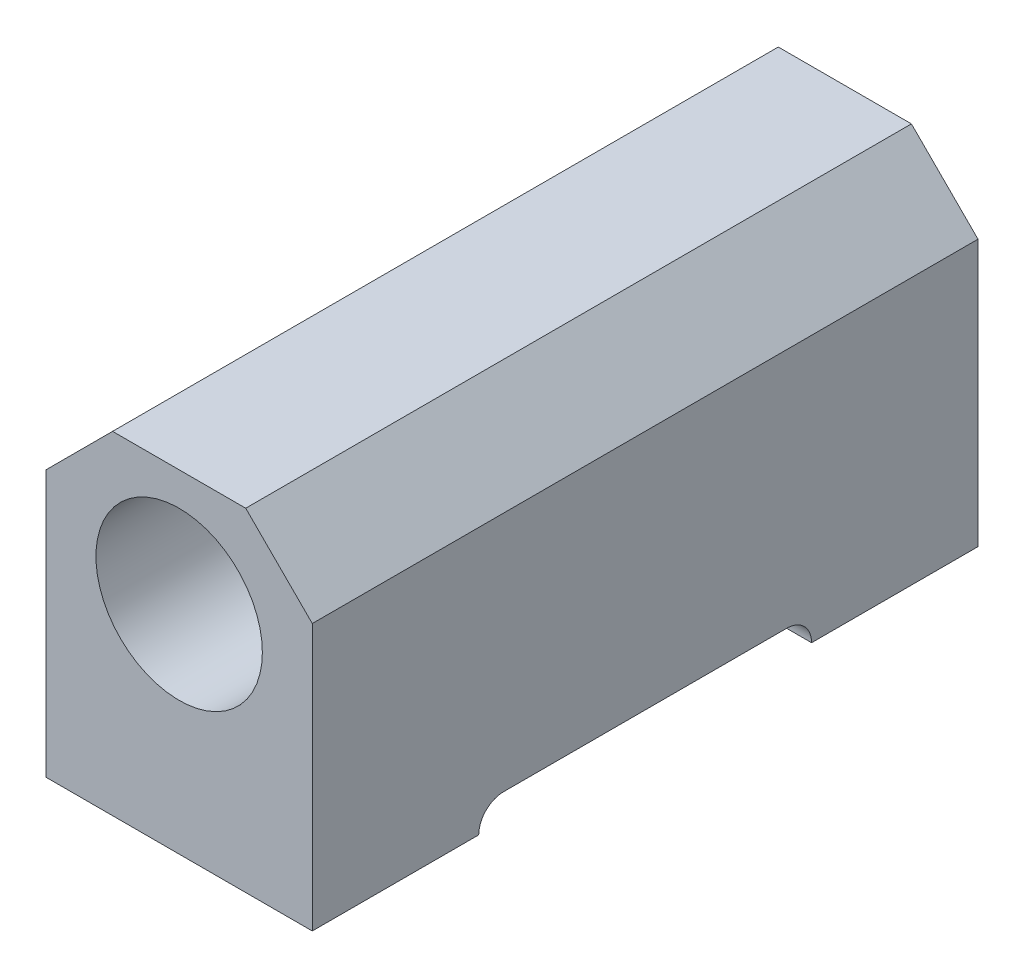
SolidWorks part; units mm, degrees
ref_plane "Plan de face" through (0, 0, 0) normal (0, 0, 1) x (1, 0, 0)
ref_plane "Plan de dessus" through (0, 0, 0) normal (0, 1, 0) x (1, 0, 0)
ref_plane "Plan de droite" through (0, 0, 0) normal (1, 0, 0) x (0, 0, -1)
sketch "Esquisse1" plane through (0, 0, 0) normal (0, 0, 1) x (1, 0, 0)
  line L0 (-16, 0) -> (16, 0)
  line L1 (16, 0) -> (16, 32)
  line L2 (16, 32) -> (8, 40)
  line L3 (8, 40) -> (-8, 40)
  line L4 (-8, 40) -> (-16, 32)
  line L5 (-16, 32) -> (-16, 0)
  line L6 (-26.6533, 32) -> (32.8789, 32) construction
  dimension "D1" = 32
  dimension "D2" = 16
  dimension "D3" = 40
  dimension "D4" = 135
  dimension "D5" = 16
extrude "Boss.-Extru.1" add sketch "Esquisse1" along normal blind 80
sketch "Esquisse2" plane through (16, 0, 0) normal (1, 0, 0) x (0, 0, -1)
  line L0 (-60, -3) -> (-60, 0)
  line L1 (-60, -3) -> (-20, -3)
  line L2 (-20, -3) -> (-20, 0)
  line L3 (-57, 3) -> (-23, 3)
  line L4 (-60, 0) -> (-13.4338, 0) construction
  line L5 (-80, 0) -> (0, 0) construction
  line L6 (-80, 0) -> (-80, 32) construction
  arc A0 (-60, 0) -> (-57, 3) centre (-57, 0) cw
  arc A1 (-20, 0) -> (-23, 3) centre (-23, 0) ccw
  dimension "D4" = 3
  dimension "D5" = 20
  dimension "D1" = 40
  dimension "D2" = 3
  dimension "D3" = 6
extrude "Enlèv. mat.-Extru.1" cut sketch "Esquisse2" against normal through all
hole_wizard "Dégagement M11" positions "Esquisse6" profile "Esquisse5" hole size "M1" standard "ISO"
sketch "Esquisse6" plane through (0, 0, 80) normal (0, 0, 1) x (1, 0, 0)
  line L0 (0, 0) -> (0, 38.5878) construction
  line L2 (-16, 0) -> (16, 0) construction
  point P0 (0, 26)
  dimension "D1" = 26
sketch "Esquisse5" plane through (0, 26, 80) normal (1, 0, 0) x (0, -1, 0)
  line L0 (0, 0) -> (0, 77.7735)
  line L1 (0, 77.7735) -> (10, 72)
  line L2 (10, 72) -> (10, 0)
  line L5 (10, 0) -> (0, 0)
  line L10 (0, 77.7735) -> (-10, 72) construction
  line L11 (0, -6.35) -> (0, 107.95) construction
  dimension "Diamètre du perçage" = 20
  dimension "Profondeur du perçage" = 72
  dimension "Angle de pointe" = 120
sketch "Esquisse3" plane through (0, 3, 0) normal (0, -1, 0) x (1, 0, 0)
  line L0 (16, 23) -> (16, 57) construction
  line L1 (-16, 80) -> (16, 80) construction
  circle A0 centre (0, 40) radius 5
  dimension "D1" = 10
  dimension "D2" = 16
  dimension "D3" = 40
extrude "Enlèv. mat.-Extru.2" cut sketch "Esquisse3" against normal up to next
sketch "Esquisse7" plane through (0, 0, 0) normal (0, -1, 0) x (1, 0, 0)
  line L0 (0, 0) -> (0, 12.9911) construction
  line L1 (-16, 0) -> (16, 0) construction
  circle A0 centre (0, 10) radius 2
  dimension "D1" = 4
  dimension "D2" = 10
extrude "Enlèv. mat.-Extru.3" cut sketch "Esquisse7" against normal up to next
